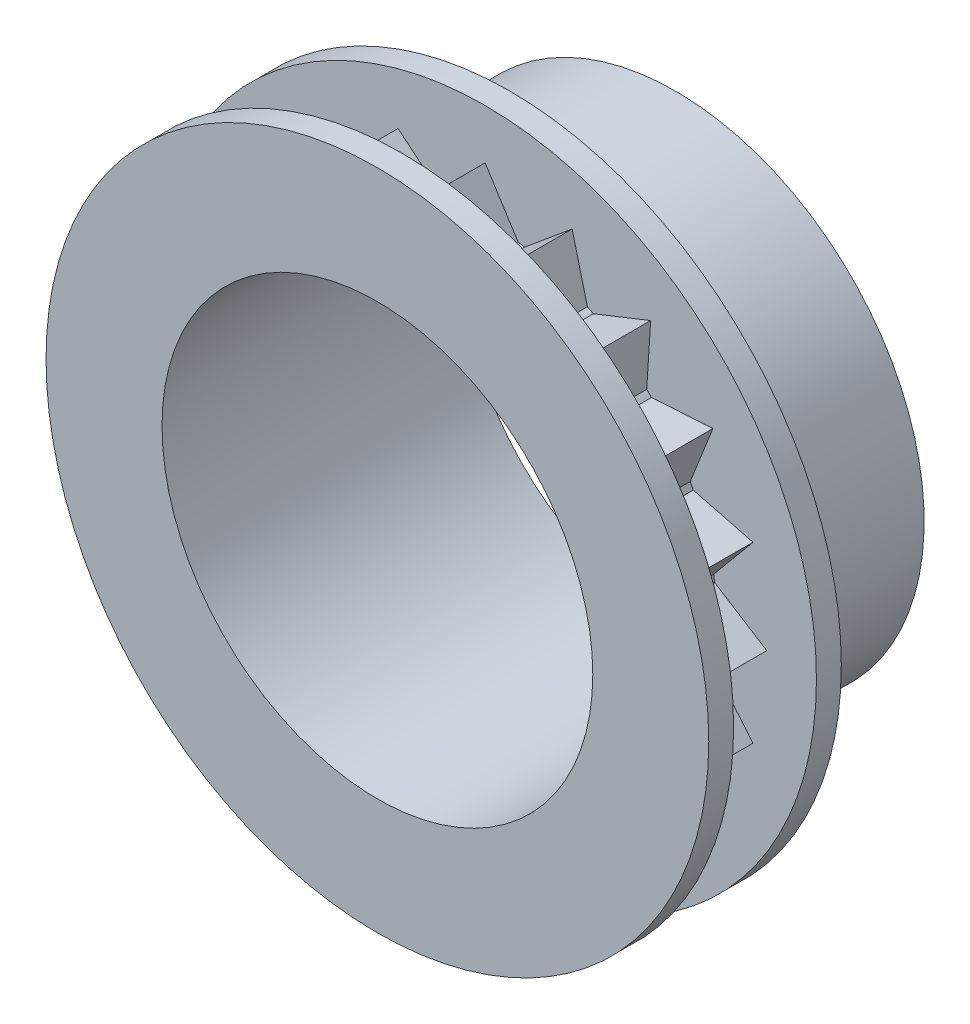
SolidWorks part; units mm, degrees
ref_plane "Front Plane" through (0, 0, 0) normal (0, 0, 1) x (1, 0, 0)
ref_plane "Top Plane" through (0, 0, 0) normal (0, 1, 0) x (1, 0, 0)
ref_plane "Right Plane" through (0, 0, 0) normal (1, 0, 0) x (0, 0, -1)
sketch "Sketch1" plane through (0, 0, 0) normal (0, 0, 1) x (1, 0, 0)
  line L0 (0, 31.211) -> (0, 12) construction
  line L1 (0, 17) -> (-1.9906, 13.8578)
  line L2 (0, 17) -> (1.9906, 13.8578)
  line L3 (5.2533, 16.168) -> (2.3891, 13.7946)
  line L4 (5.2533, 16.168) -> (6.1755, 12.5644)
  line L5 (9.9923, 13.7533) -> (6.5349, 12.3812)
  line L6 (9.9923, 13.7533) -> (9.7558, 10.0411)
  line L7 (13.7533, 9.9923) -> (10.0411, 9.7558)
  line L8 (13.7533, 9.9923) -> (12.3812, 6.5349)
  line L9 (16.168, 5.2533) -> (12.5644, 6.1755)
  line L10 (16.168, 5.2533) -> (13.7946, 2.3891)
  line L11 (17, 0) -> (13.8578, 1.9906)
  line L12 (17, 0) -> (13.8578, -1.9906)
  line L13 (16.168, -5.2533) -> (13.7946, -2.3891)
  line L14 (16.168, -5.2533) -> (12.5644, -6.1755)
  line L15 (13.7533, -9.9923) -> (12.3812, -6.5349)
  line L16 (13.7533, -9.9923) -> (10.0411, -9.7558)
  line L17 (9.9923, -13.7533) -> (9.7558, -10.0411)
  line L18 (9.9923, -13.7533) -> (6.5349, -12.3812)
  line L19 (5.2533, -16.168) -> (6.1755, -12.5644)
  line L20 (5.2533, -16.168) -> (2.3891, -13.7946)
  line L21 (0, -17) -> (1.9906, -13.8578)
  line L22 (0, -17) -> (-1.9906, -13.8578)
  line L23 (-5.2533, -16.168) -> (-2.3891, -13.7946)
  line L24 (-5.2533, -16.168) -> (-6.1755, -12.5644)
  line L25 (-9.9923, -13.7533) -> (-6.5349, -12.3812)
  line L26 (-9.9923, -13.7533) -> (-9.7558, -10.0411)
  line L27 (-13.7533, -9.9923) -> (-10.0411, -9.7558)
  line L28 (-13.7533, -9.9923) -> (-12.3812, -6.5349)
  line L29 (-16.168, -5.2533) -> (-12.5644, -6.1755)
  line L30 (-16.168, -5.2533) -> (-13.7946, -2.3891)
  line L31 (-17, 0) -> (-13.8578, -1.9906)
  line L32 (-17, 0) -> (-13.8578, 1.9906)
  line L33 (-16.168, 5.2533) -> (-13.7946, 2.3891)
  line L34 (-16.168, 5.2533) -> (-12.5644, 6.1755)
  line L35 (-13.7533, 9.9923) -> (-12.3812, 6.5349)
  line L36 (-13.7533, 9.9923) -> (-10.0411, 9.7558)
  line L37 (-9.9923, 13.7533) -> (-9.7558, 10.0411)
  line L38 (-9.9923, 13.7533) -> (-6.5349, 12.3812)
  line L39 (-5.2533, 16.168) -> (-6.1755, 12.5644)
  line L40 (-5.2533, 16.168) -> (-2.3891, 13.7946)
  line L41 (0, -17) -> (0, -21.8805) construction
  arc A0 (-13.7946, 2.3891) -> (-13.8578, 1.9906) centre (0, 0) ccw
  circle A1 centre (0, 0) radius 17
  arc A2 (-13.8578, -1.9906) -> (-13.7946, -2.3891) centre (0, 0) ccw
  arc A3 (-12.5644, -6.1755) -> (-12.3812, -6.5349) centre (0, 0) ccw
  arc A4 (-10.0411, -9.7558) -> (-9.7558, -10.0411) centre (0, 0) ccw
  arc A5 (-12.3812, 6.5349) -> (-12.5644, 6.1755) centre (0, 0) ccw
  arc A6 (-9.7558, 10.0411) -> (-10.0411, 9.7558) centre (0, 0) ccw
  arc A7 (-6.1755, 12.5644) -> (-6.5349, 12.3812) centre (0, 0) ccw
  arc A8 (-1.9906, 13.8578) -> (-2.3891, 13.7946) centre (0, 0) ccw
  arc A9 (2.3891, 13.7946) -> (1.9906, 13.8578) centre (0, 0) ccw
  arc A10 (6.5349, 12.3812) -> (6.1755, 12.5644) centre (0, 0) ccw
  arc A11 (10.0411, 9.7558) -> (9.7558, 10.0411) centre (0, 0) ccw
  arc A12 (13.7946, -2.3891) -> (13.8578, -1.9906) centre (0, 0) ccw
  arc A13 (12.3812, -6.5349) -> (12.5644, -6.1755) centre (0, 0) ccw
  arc A14 (1.9906, -13.8578) -> (2.3891, -13.7946) centre (0, 0) ccw
  arc A15 (-2.3891, -13.7946) -> (-1.9906, -13.8578) centre (0, 0) ccw
  arc A16 (-6.5349, -12.3812) -> (-6.1755, -12.5644) centre (0, 0) ccw
  arc A17 (9.7558, -10.0411) -> (10.0411, -9.7558) centre (0, 0) ccw
  arc A18 (6.1755, -12.5644) -> (6.5349, -12.3812) centre (0, 0) ccw
  arc A19 (12.5644, 6.1755) -> (12.3812, 6.5349) centre (0, 0) ccw
  arc A20 (13.8578, 1.9906) -> (13.7946, 2.3891) centre (0, 0) ccw
  point P68 (0, 0)
  dimension "D1" = 28
  dimension "D2" = 34
  dimension "D3" = 20
extrude "Boss-Extrude1" add sketch "Sketch1" along normal blind 5 contours L11 A20 L10 L9 A19 L8 L7 A11 L6 L5 A10 L4 L3 A9 L2 L1 A8 L40 L39 A7 L38 L37 A6 L36 L35 A5 L34 L33 A0 L32 L31 A2 L30 L29 A3 L28 L27 A4 L26 L25 A16 L24 L23 A15 L22 L21 A14 L20 L19 A18 L18
sketch "Sketch2" plane through (0, 0, 0) normal (0, 0, -1) x (-1, 0, 0)
  circle A0 centre (0, 0) radius 20
  dimension "D1" = 40
extrude "Boss-Extrude2" add sketch "Sketch2" along normal blind 1.5
sketch "Sketch3" plane through (0, 0, 5) normal (0, 0, 1) x (1, 0, 0)
  circle A0 centre (0, 0) radius 20
  dimension "D1" = 40
extrude "Boss-Extrude3" add sketch "Sketch3" along normal blind 1.5
sketch "Sketch4" plane through (0, 0, 6.5) normal (0, 0, 1) x (1, 0, 0)
  circle A0 centre (0, 0) radius 13
  dimension "D1" = 26
extrude "Cut-Extrude1" cut sketch "Sketch4" against normal blind 11.5
sketch "Sketch5" plane through (0, 0, -1.5) normal (0, 0, -1) x (-1, 0, 0)
  circle A0 centre (0, 0) radius 13
  circle A1 centre (0, 0) radius 15
  dimension "D1" = 30
  dimension "D2" = 26
extrude "Boss-Extrude4" add sketch "Sketch5" along normal blind 10 contours A1
sketch "Sketch6" plane through (0, 0, -11.5) normal (0, 0, -1) x (-1, 0, 0)
  circle A0 centre (0, 0) radius 13
  dimension "D1" = 26
extrude "Cut-Extrude2" cut sketch "Sketch6" against normal blind 30
